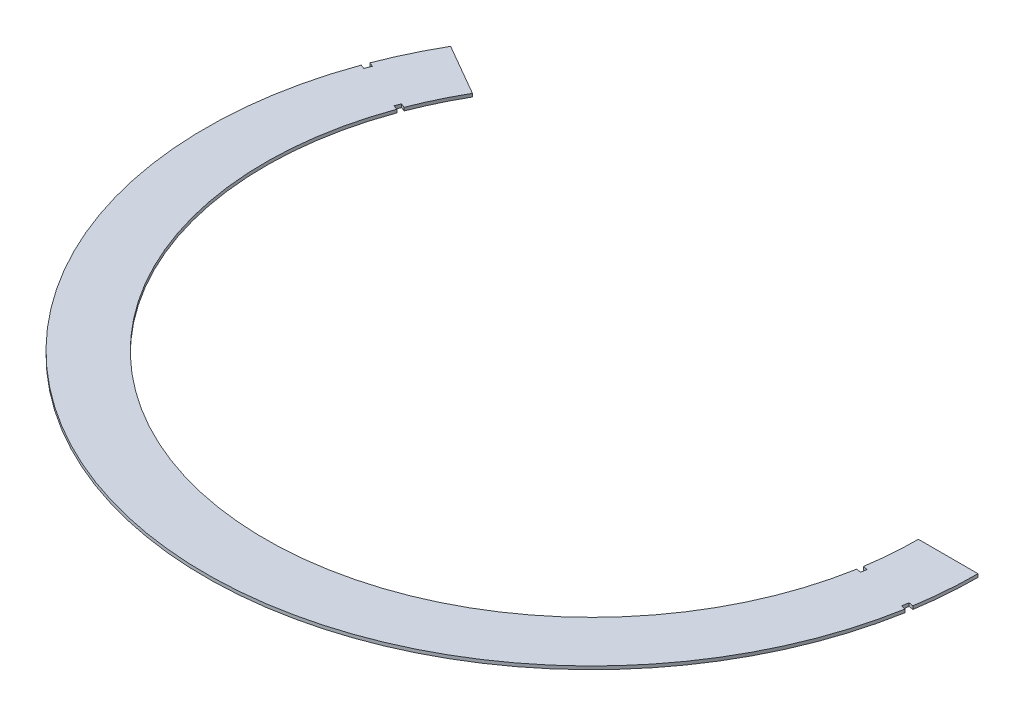
SolidWorks part; units mm, degrees
ref_plane "Front Plane" through (0, 0, 0) normal (0, 0, 1) x (1, 0, 0)
ref_plane "Top Plane" through (0, 0, 0) normal (0, 1, 0) x (1, 0, 0)
ref_plane "Right Plane" through (0, 0, 0) normal (1, 0, 0) x (0, 0, -1)
sketch "Sketch3" plane through (0, 0, 0) normal (0, 1, 0) x (1, 0, 0)
  line L0 (-61.6783, 35.61) -> (-72.9367, 42.11)
  line L1 (71.22, 0) -> (84.22, 0)
  arc A0 (-72.9367, 42.11) -> (84.22, 0) centre (0, 0) ccw
  arc A1 (71.22, 0) -> (-61.6783, 35.61) centre (0, 0) cw
  dimension "D1" = 13
  dimension "D2" = 84.22
  dimension "D3" = 150
extrude "Boss-Extrude1" add sketch "Sketch3" along normal blind 0.7
sketch "Sketch5" plane through (0, 0, 0) normal (0, 1, 0) x (1, 0, 0)
  line L0 (-66.4896, 25.523) -> (-80.4933, 30.8985)
  line L1 (-80.4933, 30.8985) -> (-81.0203, 29.489)
  line L2 (-81.0203, 29.489) -> (-66.9249, 24.3587)
  line L3 (-66.9249, 24.3587) -> (-66.4896, 25.523)
  line L4 (-61.6783, 35.61) -> (-72.9367, 42.11) construction
  arc A0 (-61.6783, 35.61) -> (71.22, 0) centre (0, 0) ccw construction
  arc A1 (-61.6783, 35.61) -> (71.22, 0) centre (0, 0) ccw construction
  dimension "D1" = 9
  dimension "D2" = 1
  dimension "D3" = 15
extrude "Cut-Extrude1" cut sketch "Sketch5" along normal through all
sketch "Sketch6" plane through (0, 0, 0) normal (0, 1, 0) x (1, 0, 0)
  line L0 (-77.6926, 29.8234) -> (-67.4232, 25.8813)
  line L1 (-77.6926, 29.8234) -> (-78.2131, 28.4673)
  line L2 (-67.4232, 25.8813) -> (-67.9437, 24.5252)
  line L3 (-78.2131, 28.4673) -> (-67.9437, 24.5252)
  line L4 (-66.4896, 25.523) -> (-78.6261, 30.1817) construction
  line L5 (-79.1409, 28.8049) -> (-66.9249, 24.3587) construction
  dimension "D1" = 1
  dimension "D2" = 1
extrude "Boss-Extrude2" add sketch "Sketch6" along normal up to surface (0.7 mm away) up to face at (13.7936, 0.7, 13.5339)
ref_plane "Plane1" through (0, 0, 0) normal (0.9659, 0, 0.2588) x (0.2588, 0, -0.9659)
mirror "Mirror1" about plane through (0, 0, 0) normal (0.9659, 0, 0.2588) of "Cut-Extrude1", "Boss-Extrude2"
